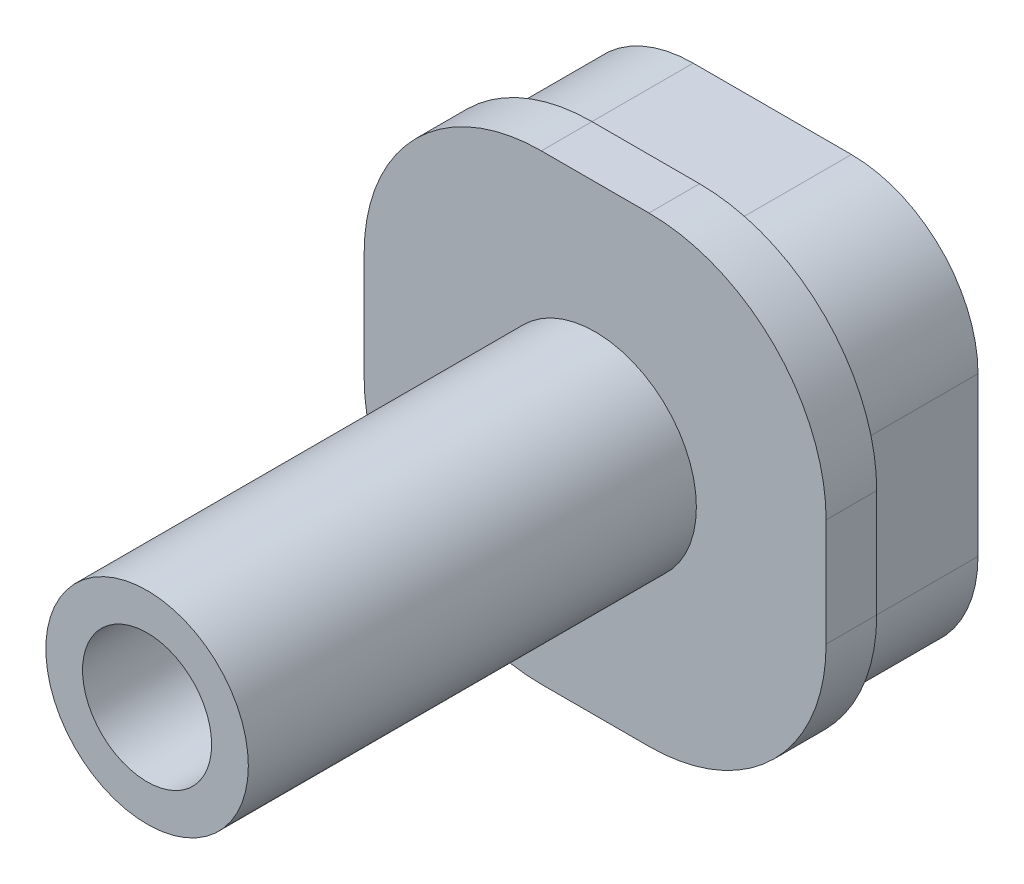
SolidWorks part; units mm, degrees
ref_plane "Płaszczyzna przednia" through (0, 0, 0) normal (0, 0, 1) x (1, 0, 0)
ref_plane "Płaszczyzna górna" through (0, 0, 0) normal (0, 1, 0) x (1, 0, 0)
ref_plane "Płaszczyzna prawa" through (0, 0, 0) normal (1, 0, 0) x (0, 0, -1)
sketch "Sketch1" plane through (0, 0, 0) normal (0, 0, 1) x (1, 0, 0)
  line L0 (6.125, 6.125) -> (-6.125, 6.125)
  line L1 (8.125, -8.125) -> (-8.125, -8.125)
  line L2 (8.125, -8.125) -> (8.125, 8.125)
  line L3 (8.125, 8.125) -> (-8.125, 8.125)
  line L4 (-8.125, -8.125) -> (-8.125, 8.125)
  line L5 (8.125, -8.125) -> (-8.125, 8.125) construction
  line L6 (8.125, 8.125) -> (-8.125, -8.125) construction
  line L7 (-6.125, -6.125) -> (-6.125, 6.125)
  line L8 (6.125, -6.125) -> (-6.125, -6.125)
  line L9 (6.125, -6.125) -> (6.125, 6.125)
  point P0 (0, 0)
  dimension "D1" = 16.25
  dimension "D2" = 2
extrude "Boss-Extrude1" add sketch "Sketch1" along normal blind 5
fillet "Fillet1" radius 5 8 edges at (-8.125, -8.125, 2.5) (8.125, -8.125, 2.5) (-8.125, 8.125, 2.5) (8.125, 8.125, 2.5) (6.125, -6.125, 2.5) (-6.125, -6.125, 2.5) (6.125, 6.125, 2.5) (-6.125, 6.125, 2.5)
sketch "Sketch2" plane through (0, 0, 5) normal (0, 0, 1) x (1, 0, 0)
  line L0 (-8.125, 3.125) -> (-8.125, -3.125) construction
  line L1 (9.125, 9.125) -> (-9.125, 9.125)
  line L2 (9.125, 9.125) -> (9.125, -9.125)
  line L3 (9.125, -9.125) -> (-9.125, -9.125)
  line L4 (-9.125, 9.125) -> (-9.125, -9.125)
  line L5 (9.125, 9.125) -> (-9.125, -9.125) construction
  line L6 (9.125, -9.125) -> (-9.125, 9.125) construction
  point P0 (0, 0)
  dimension "D1" = 1
extrude "Boss-Extrude2" add sketch "Sketch2" along normal blind 2
fillet "Fillet2" radius 7 4 edges at (9.125, -9.125, 6) (-9.125, -9.125, 6) (-9.125, 9.125, 6) (9.125, 9.125, 6)
sketch "Sketch4" plane through (0, 0, 7) normal (0, 0, 1) x (1, 0, 0)
  circle A0 centre (0, 0) radius 4
  dimension "D1" = 8
extrude "Boss-Extrude3" add sketch "Sketch4" along normal blind 17.7
sketch "Sketch6" plane through (0, 0, 24.7) normal (0, 0, 1) x (1, 0, 0)
  line L1 (0, 2.55) -> (0, -2.55) construction
  circle A0 centre (0, 0) radius 2.55
  dimension "D1" = 5.1
extrude "Cut-Extrude1" cut sketch "Sketch6" against normal offset from surface (16.7 mm away) 1 up to face at (4, 0, 7)
